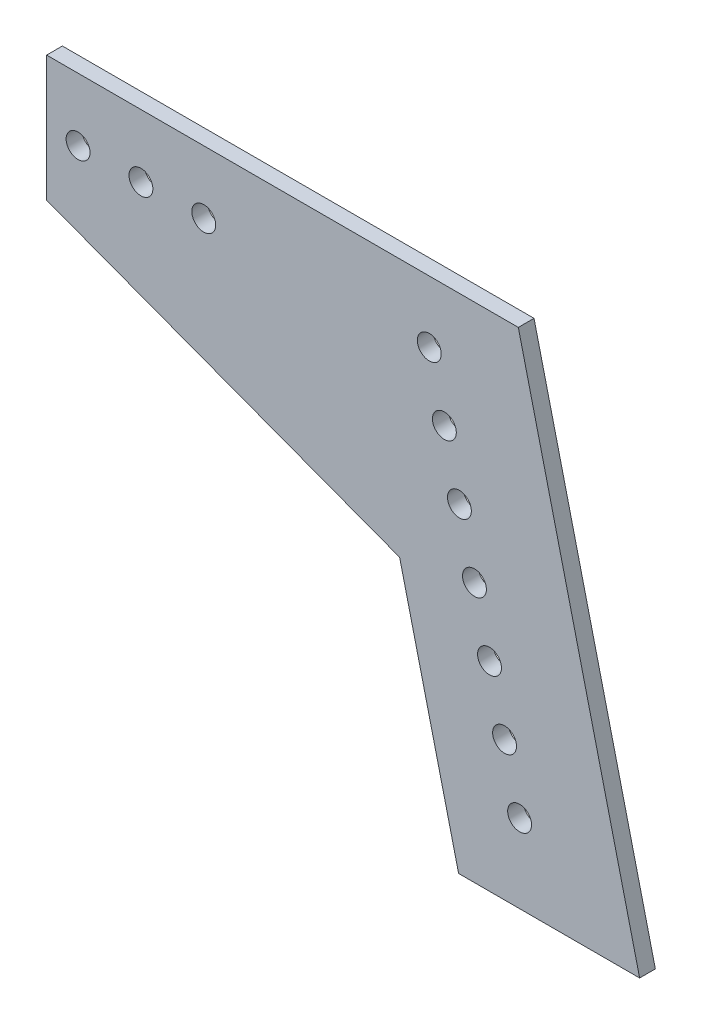
SolidWorks part; units mm, degrees
ref_plane "Front Plane" through (0, 0, 0) normal (0, 0, 1) x (1, 0, 0)
ref_plane "Top Plane" through (0, 0, 0) normal (0, 1, 0) x (1, 0, 0)
ref_plane "Right Plane" through (0, 0, 0) normal (1, 0, 0) x (0, 0, -1)
sketch "Sketch1" plane through (0, 0, 0) normal (0, 0, 1) x (1, 0, 0)
  line L1 (-190.5, -88.9) -> (190.5, -88.9)
  line L2 (-190.5, -88.9) -> (-190.5, 88.9)
  line L3 (-190.5, 88.9) -> (190.5, 88.9)
  line L4 (190.5, -88.9) -> (190.5, 88.9)
  dimension "D1" = 381
  dimension "D2" = 177.8
extrude "Boss-Extrude1" add sketch "Sketch1" along normal blind 3.175
sketch "Sketch3" plane through (0, 0, 0) normal (0, 0, -1) x (-1, 0, 0)
  line L7 (-171.2166, -74.317) -> (-133.6302, 81.448) construction
  line L8 (-263.8892, -458.3689) -> (-144.7278, 35.4576) construction
  line L9 (173.1471, -74.317) -> (135.5607, 81.448) construction
  line L10 (146.7216, 35.1951) -> (265.7441, -458.0557) construction
  line L11 (-190.5, 88.9) -> (-139.6707, 88.9)
  line L12 (-190.5, 88.9) -> (190.5, 88.9) construction
  line L13 (-139.6707, 88.9) -> (-190.5, -121.7458)
  line L14 (-190.5, -121.7458) -> (-190.5, 88.9)
  line L15 (190.5, 88.9) -> (141.6012, 88.9)
  line L16 (141.6012, 88.9) -> (190.5, -113.7455)
  line L17 (190.5, -113.7455) -> (190.5, 88.9)
  dimension "D1" = 7.62
  dimension "D2" = 7.62
extrude "Cut-Extrude1" cut sketch "Sketch3" against normal through all
sketch "Sketch4" plane through (0, 0, 0) normal (0, 0, -1) x (-1, 0, 0)
  line L0 (178.3756, -63.5) -> (-176.4452, -63.5)
  line L1 (141.6012, 88.9) -> (184.5047, -88.9) construction
  line L2 (-182.5742, -88.9) -> (-139.6707, 88.9) construction
  line L3 (-176.4452, -63.5) -> (-182.5742, -88.9)
  line L4 (-182.5742, -88.9) -> (184.5047, -88.9)
  line L5 (184.5047, -88.9) -> (178.3756, -63.5)
  dimension "D1" = 25.4
extrude "Cut-Extrude2" cut sketch "Sketch4" against normal through all
sketch "Sketch8" plane through (0, 0, 0) normal (0, 0, -1) x (-1, 0, 0)
  line L0 (-139.8645, -63.5) -> (-127.9452, -14.1181)
  line L1 (178.3756, -63.5) -> (-176.4452, -63.5) construction
  line L2 (-127.9452, -14.1181) -> (132.284, -14.1181)
  line L3 (132.284, -14.1181) -> (144.2034, -63.5)
  line L4 (144.2034, -63.5) -> (-139.8645, -63.5)
  dimension "D1" = 103.57
  dimension "D2" = 103.57
  dimension "D3" = 260.2292
  dimension "D4" = 50.8
extrude "Cut-Extrude3" cut sketch "Sketch8" against normal through all
sketch "Sketch9" plane through (0, 0, 0) normal (0, 0, -1) x (-1, 0, 0)
  line L0 (-157.7723, -70.0285) -> (-118.1899, 88.9) construction
  line L1 (-139.6707, 88.9) -> (141.6012, 88.9) construction
  line L2 (-139.8645, -63.5) -> (-176.4452, -63.5) construction
  circle A0 centre (-152.1925, -47.625) radius 2.413
  circle A1 centre (-149.1513, -35.4143) radius 2.413
  circle A2 centre (-146.1101, -23.2035) radius 2.413
  circle A3 centre (-143.069, -10.9928) radius 2.413
  circle A4 centre (-140.0278, 1.2179) radius 2.413
  circle A5 centre (-136.9866, 13.4287) radius 2.413
  circle A6 centre (-133.9454, 25.6394) radius 2.413
  circle A7 centre (-130.9042, 37.8501) radius 2.413 construction
  circle A8 centre (-127.8631, 50.0609) radius 2.413 construction
  circle A9 centre (-124.8219, 62.2716) radius 2.413
  circle A10 centre (-121.7807, 74.4823) radius 2.413
  ellipse E0 centre (-157.7823, -72.4407) end of major axis (-157.2163, -70.095) minor radius 2.3977 construction
  dimension "D1" = 4.826
  dimension "D2" = 15.875
  dimension "D3" = 11
extrude "Cut-Extrude5" cut sketch "Sketch9" against normal through all
sketch "Sketch10" plane through (0, 0, 0) normal (0, 0, -1) x (-1, 0, 0)
  line L0 (-139.6707, 88.9) -> (-151.9288, 38.1)
  line L1 (-176.4452, -63.5) -> (-139.6707, 88.9) construction
  line L2 (-151.9288, 38.1) -> (153.8593, 38.1)
  line L4 (141.6012, 88.9) -> (178.3756, -63.5) construction
  line L5 (153.8593, 38.1) -> (141.6012, 88.9)
  line L6 (141.6012, 88.9) -> (-139.6707, 88.9)
  dimension "D1" = 50.8
extrude "Cut-Extrude6" cut sketch "Sketch10" against normal through all
sketch "Sketch11" plane through (0, 0, 0) normal (0, 0, -1) x (-1, 0, 0)
  line L0 (-127.9452, -14.1181) -> (-56.6204, 12.7)
  line L1 (-56.6204, 12.7) -> (-56.6204, 38.1)
  line L2 (-151.9288, 38.1) -> (153.8593, 38.1) construction
  line L5 (-56.6204, 38.1) -> (60.9592, 38.1)
  line L6 (132.284, -14.1181) -> (-127.9452, -14.1181)
  line L7 (60.9592, 38.1) -> (153.8593, 38.1)
  line L8 (153.8593, 38.1) -> (178.3756, -63.5)
  line L9 (178.3756, -63.5) -> (144.2034, -63.5)
  line L10 (144.2034, -63.5) -> (132.284, -14.1181)
  dimension "D1" = 25.4
  dimension "D2" = 76.2
extrude "Cut-Extrude7" cut sketch "Sketch11" against normal through all
sketch "Sketch12" plane through (0, 0, 0) normal (0, 0, -1) x (-1, 0, 0)
  line L0 (-56.6204, 38.1) -> (-56.6204, 12.7) construction
  line L1 (-94.7258, 12.7) -> (108.4742, 12.7) construction
  circle A0 centre (-62.9704, 25.4) radius 2.413
  circle A1 centre (-75.6704, 25.4) radius 2.413
  circle A2 centre (-88.3704, 25.4) radius 2.413
  dimension "D1" = 4.826
  dimension "D2" = 6.35
  dimension "D3" = 12.7
  dimension "D4" = 3
extrude "Cut-Extrude8" cut sketch "Sketch12" against normal through all
sketch "Sketch7" plane through (0, 0, 0) normal (0, 0, -1) x (-1, 0, 0)
  line L0 (-142.1813, -63.5) -> (-127.8939, -16.9599)
  line L1 (179.0525, -63.5) -> (-177.122, -63.5) construction
  line L2 (-127.8939, -16.9599) -> (126.8526, -16.9599)
  line L3 (126.8526, -16.9599) -> (140.6477, -63.5)
  line L4 (140.6477, -63.5) -> (-142.1813, -63.5)
sketch "Sketch6" plane through (0, 0, 0) normal (0, 0, -1) x (-1, 0, 0)
  line L0 (-140.8106, -63.5) -> (-127.3051, -19.1804)
  line L1 (179.0525, -63.5) -> (-177.122, -63.5) construction
  line L2 (-127.3051, -19.1804) -> (124.3177, -19.1804)
  line L3 (124.3177, -19.1804) -> (136.9873, -63.5)
